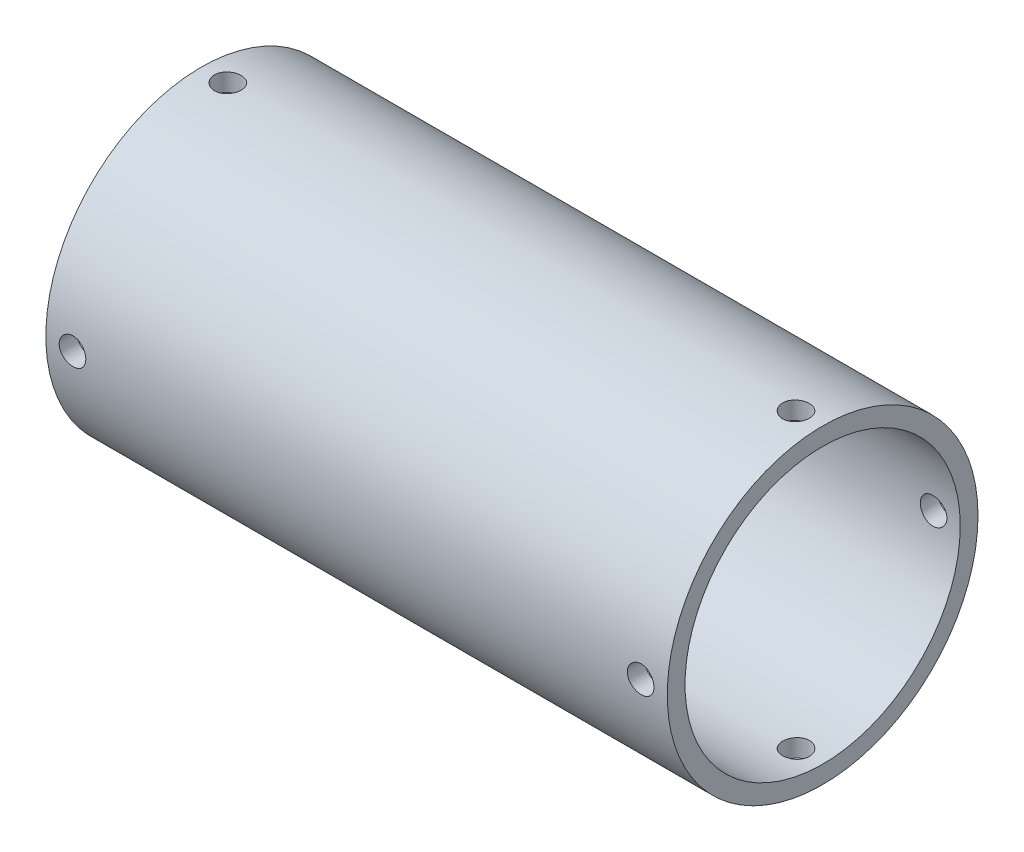
SolidWorks part; units mm, degrees
ref_plane "Спереди" through (0, 0, 0) normal (0, 0, 1) x (1, 0, 0)
ref_plane "Сверху" through (0, 0, 0) normal (0, 1, 0) x (1, 0, 0)
ref_plane "Справа" through (0, 0, 0) normal (1, 0, 0) x (0, 0, -1)
sketch "Эскиз1" plane through (0, 0, 0) normal (1, 0, 0) x (0, 0, -1)
  circle A0 centre (0, 0) radius 17.5
  circle A1 centre (0, 0) radius 15.5
  dimension "D1" = 35
  dimension "D2" = 31
extrude "Бобышка-Вытянуть1" add sketch "Эскиз1" along normal blind 70
sketch "Эскиз2" plane through (0, 0, 0) normal (0, 0, 1) x (1, 0, 0)
  line L0 (70, -17.5) -> (70, 17.5) construction
  line L1 (9.528, 0) -> (21.5106, 0)
  circle A0 centre (3, 0) radius 1.5
  circle A1 centre (67, 0) radius 1.5
  dimension "D1" = 3
  dimension "D2" = 3
  dimension "D3" = 3
  dimension "D4" = 3
extrude "Вырез-Вытянуть1" cut sketch "Эскиз2" against normal through all both and the other way through all contours A0 | A1
pattern_circular "Круговой массив1" count 2 every 90 about axis through (9.528, 0, 0) along (1, 0, 0) of "Вырез-Вытянуть1"
